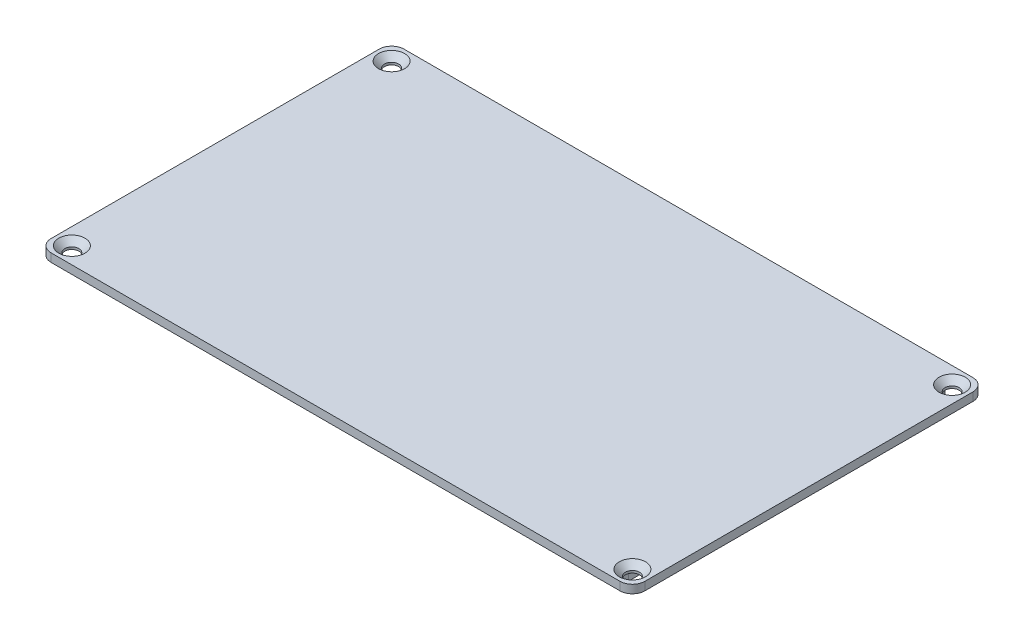
SolidWorks part; units mm, degrees
ref_plane "Ebene vorne" through (0, 0, 0) normal (0, 0, 1) x (1, 0, 0)
ref_plane "Ebene oben" through (0, 0, 0) normal (0, 1, 0) x (1, 0, 0)
ref_plane "Ebene rechts" through (0, 0, 0) normal (1, 0, 0) x (0, 0, -1)
sketch "Skizze1" plane through (0, 0, 0) normal (0, 1, 0) x (1, 0, 0)
  line L1 (0, 0) -> (131, 0)
  line L2 (0, 0) -> (0, 81)
  line L3 (0, 81) -> (131, 81)
  line L4 (131, 0) -> (131, 81)
  line L5 (2, 2) -> (129, 2)
  line L6 (2, 2) -> (2, 79)
  line L7 (2, 79) -> (129, 79)
  line L8 (129, 2) -> (129, 79)
  dimension "D1" = 131
  dimension "D2" = 81
  dimension "D3" = 2
  dimension "D4" = 2
  dimension "D5" = 2
  dimension "D6" = 2
extrude "Aufsatz-Linear austragen1" add sketch "Skizze1" along normal blind 2
sketch "Skizze2" plane through (0, 2, 0) normal (0, 1, 0) x (1, 0, 0)
  line L0 (0, 81) -> (0, 0) construction
  line L1 (-6, -2) -> (137, -2)
  line L2 (-6, -2) -> (-6, 83)
  line L3 (-6, 83) -> (137, 83)
  line L4 (137, -2) -> (137, 83)
  line L5 (131, 0) -> (131, 81) construction
  line L6 (131, 81) -> (0, 81) construction
  line L7 (0, 0) -> (131, 0) construction
  dimension "D1" = 6
  dimension "D2" = 6
  dimension "D3" = 2
  dimension "D4" = 2
extrude "Aufsatz-Linear austragen2" add sketch "Skizze2" along normal blind 2
fillet "Verrundung1" radius 3 8 edges at (137, 3, 2) (137, 3, -83) (-6, 3, -83) (-6, 3, 2) (0, 1, 0) (0, 1, -81) (131, 1, -81) (131, 1, 0)
hole_wizard "Formsenkung für M3 Linsensenkschraube mit Schlitz1" positions "Skizze3" profile "Skizze4" countersink size "M3" standard "DIN"
sketch "Skizze3" plane through (0, 4, 0) normal (0, 1, 0) x (1, 0, 0)
  line L1 (-2, 2) -> (133, 2) construction
  line L2 (-2, 2) -> (-2, 79) construction
  line L3 (-2, 79) -> (133, 79) construction
  line L4 (133, 2) -> (133, 79) construction
  line L5 (-6, 80) -> (-6, 1) construction
  line L6 (137, 1) -> (137, 80) construction
  line L7 (134, 83) -> (-3, 83) construction
  line L8 (-3, -2) -> (134, -2) construction
  point P0 (-2, 2)
  point P1 (133, 79)
  point P128 (-2, 79)
  point P129 (133, 2)
  dimension "D1" = 4
  dimension "D2" = 4
  dimension "D3" = 4
  dimension "D4" = 4
sketch "Skizze4" plane through (-2, 4, -2) normal (1, 0, 0) x (0, 0, 1)
  line L0 (0, 0) -> (0, 8.2715)
  line L1 (0, 8.2715) -> (1.7, 7.25)
  line L2 (1.7, 7.25) -> (1.7, 1.45)
  line L3 (1.7, 1.45) -> (3.15, 0)
  line L5 (3.15, 0) -> (0, 0)
  line L6 (-1.7, 1.45) -> (-3.15, 0) construction
  line L10 (0, 8.2715) -> (-1.7, 7.25) construction
  line L11 (0, -6.35) -> (0, 107.95) construction
  dimension "Bohrerdurchmesser" = 3.4
  dimension "Bohrungstiefe" = 7.25
  dimension "Senkdurchmesser (Oben)" = 6.3
  dimension "Senkwinkel (Oben)" = 90
  dimension "Spitzenwinkel" = 118
